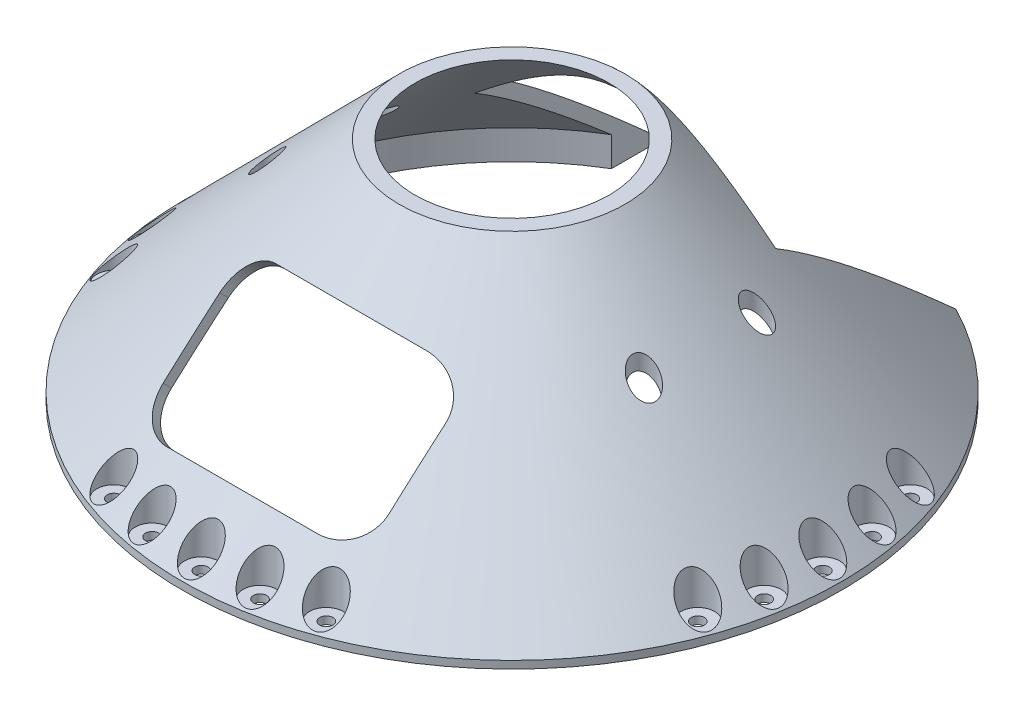
SolidWorks part; units mm, degrees
ref_plane "Front Plane" through (0, 0, 0) normal (0, 0, 1) x (1, 0, 0)
ref_plane "Top Plane" through (0, 0, 0) normal (0, 1, 0) x (1, 0, 0)
ref_plane "Right Plane" through (0, 0, 0) normal (1, 0, 0) x (0, 0, -1)
sketch "Sketch1" plane through (0, 0, 0) normal (0, 0, 1) x (1, 0, 0)
  line L0 (0, 0) -> (87.5, 0)
  line L1 (87.5, 0) -> (87.5, 2)
  line L2 (87.5, 2) -> (30, 60)
  line L3 (30, 60) -> (0, 60)
  line L4 (0, 60) -> (0, 0)
  point P6 (30.5992, 53.9784)
  point P7 (0, 51.5717)
  dimension "D1" = 87.5
  dimension "D2" = 60
  dimension "D3" = 30
  dimension "D4" = 2
revolve "Revolve1" add sketch "Sketch1" angle 360 about L4
shell "Shell1" thickness 3
sketch "Sketch2" plane through (0, 0, 0) normal (0, 1, 0) x (1, 0, 0)
  circle A0 centre (0, 0) radius 87.5 construction
  circle A1 centre (0, 0) radius 87.5
  circle A2 centre (0, 0) radius 77.5
  dimension "D1" = 10
extrude "Boss-Extrude1" add sketch "Sketch2" along normal up to next
sketch "Sketch3" plane through (0, 0, 0) normal (0, 1, 0) x (1, 0, 0)
  line L1 (-40, 145) -> (40, 145)
  line L2 (-40, 145) -> (-40, 30)
  line L3 (-40, 30) -> (40, 30)
  line L4 (40, 145) -> (40, 30)
  line L5 (-40, 145) -> (40, 30) construction
  line L6 (-40, 30) -> (40, 145) construction
  circle A0 centre (0, 0) radius 87.5 construction
  point P0 (0, 87.5)
  dimension "D1" = 80
  dimension "D2" = 115
extrude "Cut-Extrude1" cut sketch "Sketch3" along normal through all
ref_plane "Plane1" through (0, 2, 0) normal (0, 1, 0) x (1, 0, 0)
sketch "Sketch4" plane through (0, 2, 0) normal (0, 1, 0) x (1, 0, 0)
  line L0 (-82.5, 0) -> (0, 0) construction
  circle A0 centre (-82.5, 0) radius 4.5
  dimension "D2" = 9
  dimension "D1" = 82.5
extrude "Cut-Extrude2" cut sketch "Sketch4" along normal through all
sketch "Sketch5" plane through (0, 2, 0) normal (0, 1, 0) x (1, 0, 0)
  circle A0 centre (-82.5, 0) radius 1.75
  dimension "D1" = 3.5
extrude "Cut-Extrude3" cut sketch "Sketch5" against normal through all
pattern_circular "CirPattern1" count 3 every 10 about axis through (0, 0, 0) along (0, 1, 0) of "Cut-Extrude3", "Cut-Extrude2"
pattern_circular "CirPattern2" count 3 every 90 about axis through (0, 2, 0) along (0, 1, 0) of "CirPattern1", "Cut-Extrude2", "Cut-Extrude3"
ref_plane "Plane2" through (0, 0, 0) normal (0, 0.7071, 0.7071) x (1, 0, 0)
sketch "Sketch6" plane through (0, 0, 0) normal (0, 0.7071, 0.7071) x (1, 0, 0)
  line L0 (0, 0) -> (0, -20) construction
  line L1 (-20, -40) -> (20, -40)
  line L2 (-30, -30) -> (-30, -10)
  line L3 (-20, 0) -> (20, 0)
  line L4 (30, -30) -> (30, -10)
  line L5 (-30, -40) -> (30, 0) construction
  line L6 (-30, 0) -> (30, -40) construction
  arc A0 (20, 0) -> (30, -10) centre (20, -10) cw
  arc A1 (20, -40) -> (30, -30) centre (20, -30) ccw
  arc A2 (-20, -40) -> (-30, -30) centre (-20, -30) cw
  arc A3 (-30, -10) -> (-20, 0) centre (-20, -10) cw
  point P0 (0, -20)
  dimension "D4" = 10
  dimension "D1" = 60
  dimension "D2" = 40
  dimension "D3" = 20
extrude "Cut-Extrude4" cut sketch "Sketch6" along normal through all
sketch "Sketch7" plane through (0, 0, 0) normal (0, 1, 0) x (1, 0, 0)
  line L1 (-50, 15) -> (50, 15) construction
  line L2 (-50, 15) -> (-50, -15) construction
  line L3 (-50, -15) -> (50, -15) construction
  line L4 (50, 15) -> (50, -15) construction
  line L5 (-50, 15) -> (50, -15) construction
  line L6 (-50, -15) -> (50, 15) construction
  line L7 (15, 50) -> (-15, 50) construction
  line L8 (15, 50) -> (15, -50) construction
  line L9 (15, -50) -> (-15, -50) construction
  line L10 (-15, 50) -> (-15, -50) construction
  line L11 (15, 50) -> (-15, -50) construction
  line L12 (15, -50) -> (-15, 50) construction
  circle A0 centre (-50, 15) radius 3.5
  circle A1 centre (-50, -15) radius 3.5
  circle A2 centre (50, -15) radius 3.5
  circle A3 centre (50, 15) radius 3.5
  circle A4 centre (15, -50) radius 3.5
  circle A5 centre (-15, -50) radius 3.5
  point P0 (0, 0)
  point P6 (0, 0)
  dimension "D3" = 7
  dimension "D1" = 100
  dimension "D2" = 30
extrude "Cut-Extrude5" cut sketch "Sketch7" along normal through all
